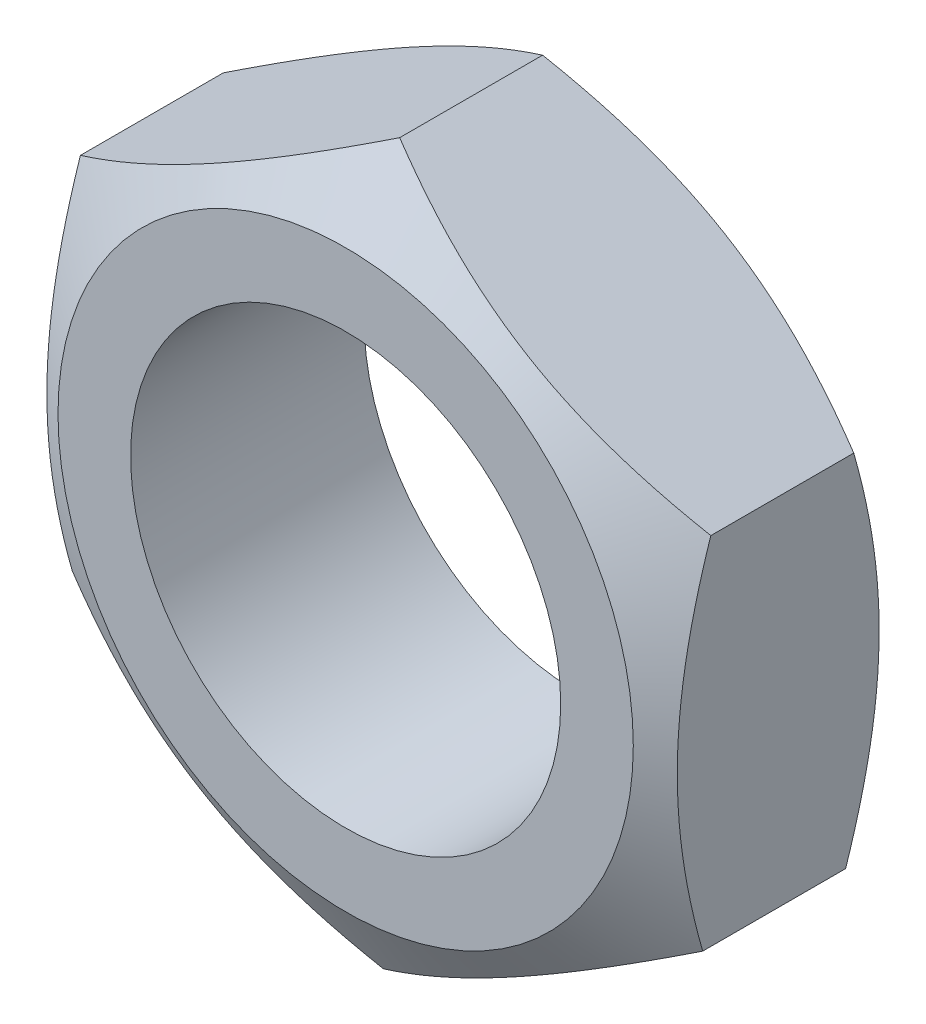
SolidWorks part; units mm, degrees
ref_plane "Alzado" through (0, 0, 0) normal (0, 0, 1) x (1, 0, 0)
ref_plane "Planta" through (0, 0, 0) normal (0, 1, 0) x (1, 0, 0)
ref_plane "Vista lateral" through (0, 0, 0) normal (1, 0, 0) x (0, 0, -1)
sketch "Croquis1" plane through (0, 0, 0) normal (0, 0, 1) x (1, 0, 0)
  line L1 (-13.3226, 8.0938) -> (-13.6707, -7.4908)
  line L2 (-13.6707, -7.4908) -> (-0.3481, -15.5846)
  line L3 (-0.3481, -15.5846) -> (13.3226, -8.0938)
  line L4 (13.3226, -8.0938) -> (13.6707, 7.4908)
  line L5 (13.6707, 7.4908) -> (0.3481, 15.5846)
  line L6 (0.3481, 15.5846) -> (-13.3226, 8.0938)
  circle A0 centre (0, 0) radius 9.209
  circle A1 centre (0, 0) radius 13.5 construction
  dimension "D1" = 27
extrude "Saliente-Extruir1" add sketch "Croquis1" along normal blind 10
sketch "Croquis2" plane through (0, 0, 10) normal (0, 0, 1) x (1, 0, 0)
  circle A0 centre (0, 0) radius 12.317
  circle A1 centre (0, 0) radius 30.3297
extrude "Cortar-Extruir1" cut sketch "Croquis2" against normal blind 10 draft 59
sketch "Croquis3" plane through (0, 0, 0) normal (0, 0, -1) x (-1, 0, 0)
  circle A0 centre (0, 0) radius 12.4019
  circle A1 centre (0, 0) radius 29.0141
extrude "Cortar-Extruir2" cut sketch "Croquis3" against normal blind 10 draft 59
